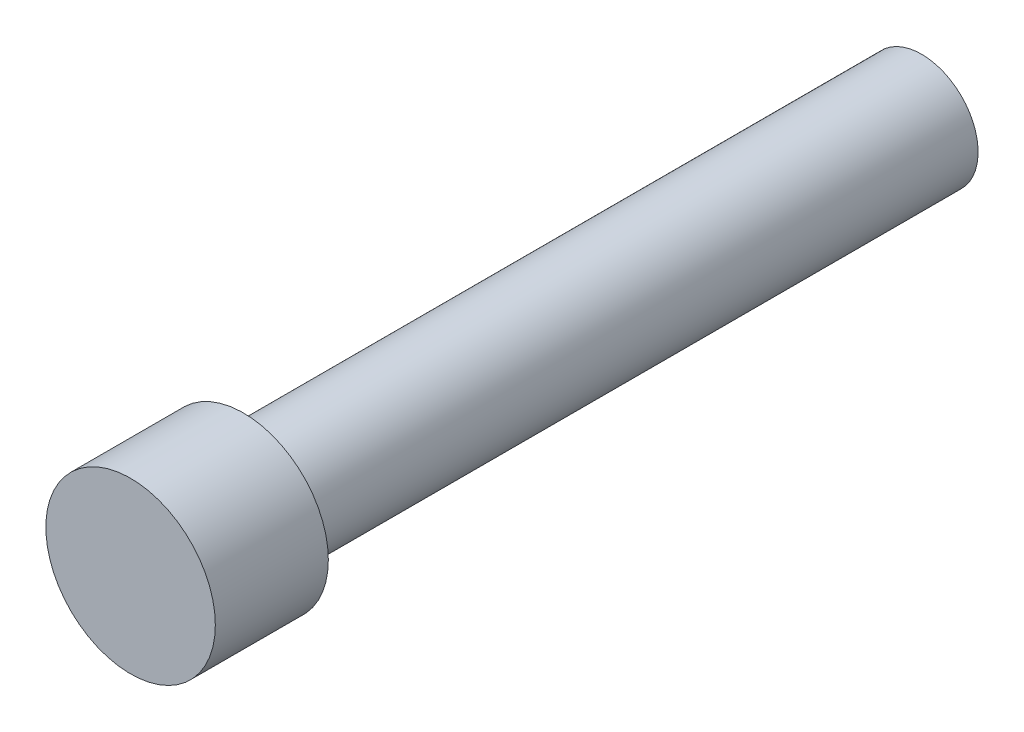
SolidWorks part; units mm, degrees
ref_plane "前视基准面" through (0, 0, 0) normal (0, 0, 1) x (1, 0, 0)
ref_plane "上视基准面" through (0, 0, 0) normal (0, 1, 0) x (1, 0, 0)
ref_plane "右视基准面" through (0, 0, 0) normal (1, 0, 0) x (0, 0, -1)
sketch "草图1" plane through (0, 0, 0) normal (0, 0, 1) x (1, 0, 0)
  circle A0 centre (0, 0) radius 1.5
  dimension "D1" = 3
extrude "凸台-拉伸1" add sketch "草图1" along normal blind 2
sketch "草图2" plane through (0, 0, 0) normal (0, 0, -1) x (-1, 0, 0)
  circle A0 centre (0, 0) radius 1
  dimension "D1" = 2
extrude "凸台-拉伸3" add sketch "草图2" along normal blind 12
